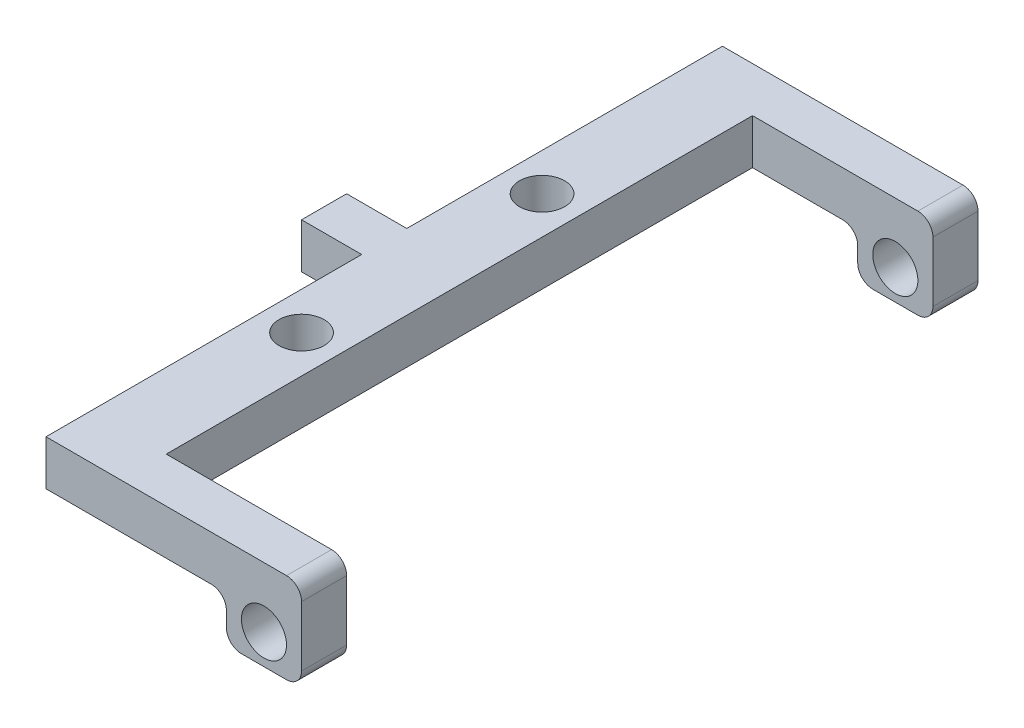
SolidWorks part; units mm, degrees
ref_plane "前视基准面" through (0, 0, 0) normal (0, 0, 1) x (1, 0, 0)
ref_plane "上视基准面" through (0, 0, 0) normal (0, 1, 0) x (1, 0, 0)
ref_plane "右视基准面" through (0, 0, 0) normal (1, 0, 0) x (0, 0, -1)
sketch "草图1" plane through (0, 0, 0) normal (0, 1, 0) x (1, 0, 0)
  line L0 (-2.5, -1.5) -> (-2.5, -10.5)
  line L1 (-2.5, 10.5) -> (2.5, 10.5)
  line L2 (-2.5, 10.5) -> (-2.5, 1.5)
  line L3 (-2.5, -10.5) -> (2.5, -10.5)
  line L4 (2.5, 10.5) -> (2.5, -10.5)
  line L5 (-2.5, 10.5) -> (-0.3571, 1.5) construction
  line L6 (-2.5, -10.5) -> (0, 0) construction
  line L7 (-6.5, 1.5) -> (-2.5, 1.5)
  line L8 (-6.5, 1.5) -> (-6.5, -1.5)
  line L9 (-6.5, -1.5) -> (-2.5, -1.5)
  line L11 (-6.5, 1.5) -> (2.5, -0.5769) construction
  line L12 (-2.5, -0.5769) -> (2.5, 0.5769) construction
  line L14 (0, 0) -> (2.5, -10.5) construction
  circle A0 centre (0, 8) radius 1.5
  circle A1 centre (0, -8) radius 1.5
  point P0 (0, 0)
  point P10 (0, 0)
  dimension "D3" = 3
  dimension "D4" = 8
  dimension "D5" = 3
  dimension "D6" = 8
  dimension "D1" = 5
  dimension "D2" = 21
  dimension "D7" = 3
  dimension "D8" = 4
extrude "凸台-拉伸1" add sketch "草图1" along normal blind 3
sketch "草图3" plane through (0, 3, 0) normal (0, 1, 0) x (1, 0, 0)
  line L0 (-2.5, 10.5) -> (-2.5, 22.5)
  line L1 (-2.5, 22.5) -> (2.5, 22.5)
  line L2 (2.5, 10.5) -> (2.5, 22.5)
  line L3 (-2.5, 10.5) -> (2.5, 10.5)
  line L4 (0, 0) -> (8.3289, 0) construction
  line L5 (-2.5, -10.5) -> (2.5, -10.5)
  line L6 (2.5, -10.5) -> (2.5, -22.5)
  line L7 (-2.5, -22.5) -> (2.5, -22.5)
  line L8 (-2.5, -10.5) -> (-2.5, -22.5)
  dimension "D1" = 22.5
extrude "凸台-拉伸2" add sketch "草图3" against normal blind 3
sketch "草图4" plane through (0, 0, -22.5) normal (0, 0, -1) x (-1, 0, 0)
  line L0 (-2.5, 3) -> (-13.5, 3)
  line L1 (-14.5, 2) -> (-14.5, -2)
  line L2 (-13.5, -3) -> (-10.5, -3)
  line L3 (-9.5, -2) -> (-9.5, -1)
  line L4 (-8.5, 0) -> (-2.5, 0)
  line L5 (-12, -3) -> (-12, -1) construction
  line L6 (-2.5, 3) -> (-2.5, 0)
  circle A0 centre (-12, -1) radius 1.5
  arc A1 (-13.5, -3) -> (-14.5, -2) centre (-13.5, -2) cw
  arc A2 (-10.5, -3) -> (-9.5, -2) centre (-10.5, -2) ccw
  arc A3 (-9.5, -1) -> (-8.5, 0) centre (-8.5, -1) cw
  arc A4 (-13.5, 3) -> (-14.5, 2) centre (-13.5, 2) ccw
  point P13 (-14.5, -3)
  point P16 (-9.5, -3)
  point P21 (-14.5, 3)
  dimension "D4" = 3
  dimension "D6" = 1
  dimension "D1" = 12
  dimension "D2" = 5
  dimension "D3" = 6
  dimension "D5" = 2
extrude "凸台-拉伸3" add sketch "草图4" against normal blind 3
mirror "镜向1" about plane through (0, 0, 0) normal (0, 0, 1) of "凸台-拉伸3"
